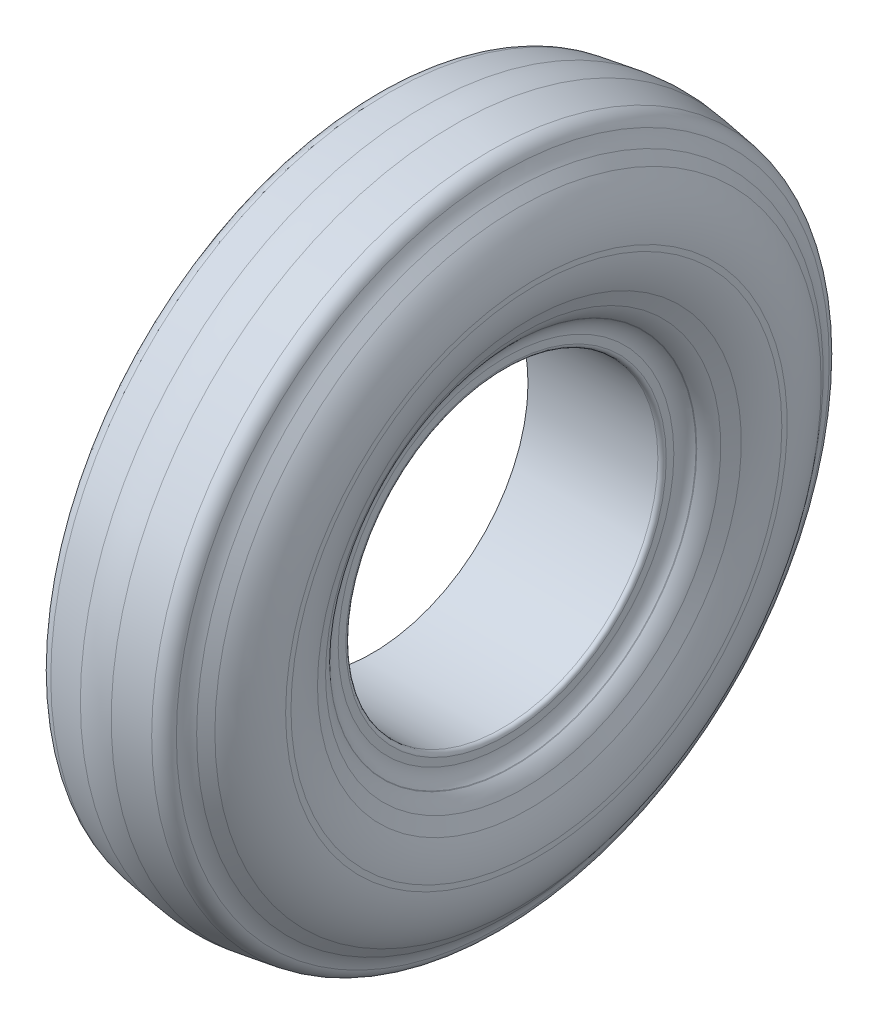
SolidWorks part; units mm, degrees
material "BUTYL"
ref_plane "Front Plane" through (0, 0, 0) normal (0, 0, 1) x (1, 0, 0)
ref_plane "Top Plane" through (0, 0, 0) normal (0, 1, 0) x (1, 0, 0)
ref_plane "Right Plane" through (0, 0, 0) normal (1, 0, 0) x (0, 0, -1)
sketch "Sketch2" plane through (0, 0, 0) normal (0, 0, 1) x (1, 0, 0)
  line L0 (0, 94.615) -> (40.64, 94.615) construction
  line L1 (40.64, 94.615) -> (40.64, 107.315)
  line L2 (40.64, 107.315) -> (48.895, 114.935)
  line L3 (48.895, 114.935) -> (59.055, 138.2145)
  line L4 (59.055, 138.2145) -> (59.055, 169.8816)
  line L5 (59.055, 169.8816) -> (40.005, 193.675)
  line L6 (40.005, 193.675) -> (36.83, 203.835)
  line L7 (36.83, 203.835) -> (0, 209.55)
  line L8 (0, 94.615) -> (0, 413.0168) construction
  line L9 (0, 0) -> (0, 94.615) construction
  line L10 (0, 94.615) -> (-40.64, 94.615) construction
  line L11 (-36.83, 203.835) -> (0, 209.55)
  line L12 (-40.005, 193.675) -> (-36.83, 203.835)
  line L13 (-59.055, 169.8816) -> (-40.005, 193.675)
  line L14 (-59.055, 138.2145) -> (-59.055, 169.8816)
  line L15 (-48.895, 114.935) -> (-59.055, 138.2145)
  line L16 (-40.64, 107.315) -> (-48.895, 114.935)
  line L17 (-40.64, 94.615) -> (-40.64, 107.315)
  line L18 (40.64, 94.615) -> (-40.64, 94.615)
  line L19 (0, 0) -> (137.0427, 0) construction
  dimension "D1" = 40.64
  dimension "D2" = 12.7
  dimension "D3" = 59.055
  dimension "D4" = 7.62
  dimension "D5" = 25.4
  dimension "D6" = 48.895
  dimension "D7" = 99.06
  dimension "D8" = 109.22
  dimension "D9" = 94.615
  dimension "D10" = 36.83
  dimension "D11" = 40.005
  dimension "D12" = 209.55
  dimension "D13" = 30.48
revolve "Revolve2" add sketch "Sketch2" angle 360 about L19
fillet "Fillet1" radius 12.7 2 edges at (40.64, 0, 107.315) (-40.64, 0, 107.315)
fillet "Fillet2" radius 25.4 2 edges at (48.895, 0, 114.935) (-48.895, 0, 114.935)
fillet "Fillet3" radius 50.8 2 edges at (59.055, 0, 138.2145) (-59.055, 0, 138.2145)
fillet "Fillet4" radius 50.8 2 edges at (59.055, 0, 169.8816) (-59.055, 0, 169.8816)
fillet "Fillet5" radius 25.4 2 edges at (40.005, 0, 193.675) (-40.005, 0, 193.675)
fillet "Fillet6" radius 10.16 2 edges at (36.83, 0, 203.835) (-36.83, 0, 203.835)
fillet "Fillet7" radius 60.96 1 edges at (0, 0, 209.55)
fillet "Fillet8" radius 2.54 1 edges at (40.64, 0, 94.615)
